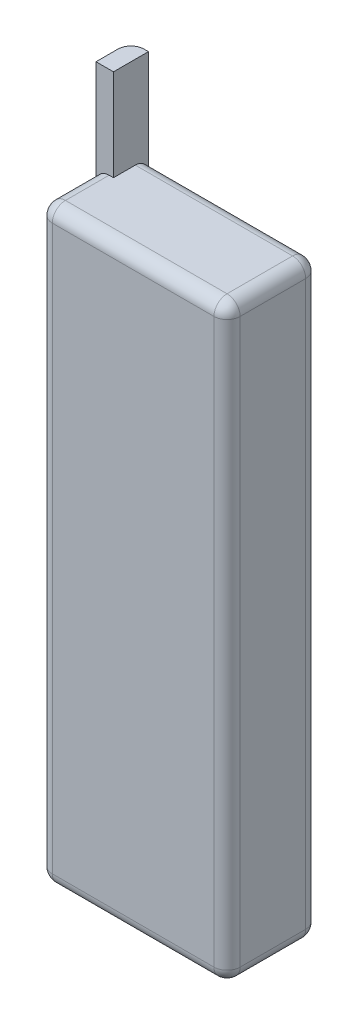
SolidWorks part; units mm, degrees
ref_plane "Plano frontal" through (0, 0, 0) normal (0, 0, 1) x (1, 0, 0)
ref_plane "Plano superior" through (0, 0, 0) normal (0, 1, 0) x (1, 0, 0)
ref_plane "Plano direito" through (0, 0, 0) normal (1, 0, 0) x (0, 0, -1)
sketch "Esboço1" plane through (0, 0, 0) normal (0, 0, 1) x (1, 0, 0)
  line L1 (0, 0) -> (43, 0)
  line L2 (0, 0) -> (0, 135)
  line L3 (0, 135) -> (43, 135)
  line L4 (43, 0) -> (43, 135)
  dimension "D1" = 135
  dimension "D2" = 43
extrude "Ressalto-extrusão1" add sketch "Esboço1" along normal blind 21
sketch "Esboço2" plane through (0, 135, 0) normal (0, 1, 0) x (1, 0, 0)
  line L0 (43, 0) -> (0, 0) construction
  line L1 (0, 0) -> (4, 0)
  line L2 (0, 0) -> (0, -8)
  line L3 (0, -8) -> (4, -8)
  line L4 (4, 0) -> (4, -8)
  line L5 (0, -21) -> (0, 0) construction
  point P5 (0, 0)
  point P6 (0, 0)
  dimension "D1" = 4
  dimension "D2" = 8
extrude "Ressalto-extrusão2" add sketch "Esboço2" along normal blind 21
fillet "Filete2" radius 3 8 edges at (0, 0, 10.5) (21.5, 0, 21) (43, 0, 10.5) (21.5, 0, 0) (0, 78, 0) (43, 67.5, 0) (0, 67.5, 21) (43, 67.5, 21)
fillet "Filete3" radius 3 7 edges at (42.1213, 135, 0.8787) (42.1213, 135, 20.1213) (0.8787, 135, 20.1213) (22, 135, 0) (43, 135, 10.5) (0, 135, 13) (21.5, 135, 21)
